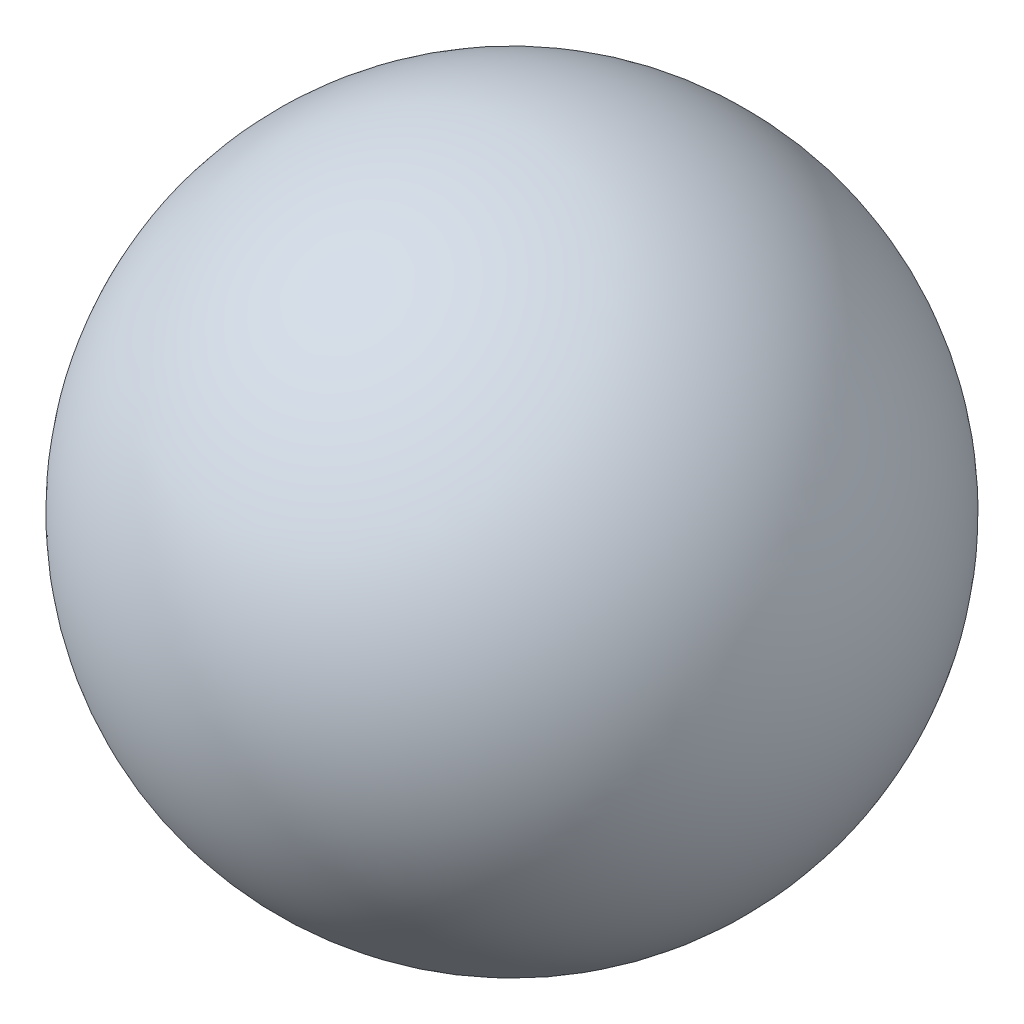
SolidWorks part; units mm, degrees
ref_plane "Plano frontal" through (0, 0, 0) normal (0, 0, 1) x (1, 0, 0)
ref_plane "Plano superior" through (0, 0, 0) normal (0, 1, 0) x (1, 0, 0)
ref_plane "Plano direito" through (0, 0, 0) normal (1, 0, 0) x (0, 0, -1)
sketch "Esboço1" plane through (0, 0, 0) normal (0, 0, 1) x (1, 0, 0)
  line L0 (-4.745, 0) -> (4.745, 0)
  arc A0 (4.745, 0) -> (-4.745, 0) centre (0, 0) ccw
  dimension "D1" = 9.49
revolve "Revolução1" add sketch "Esboço1" angle 360 about L0
